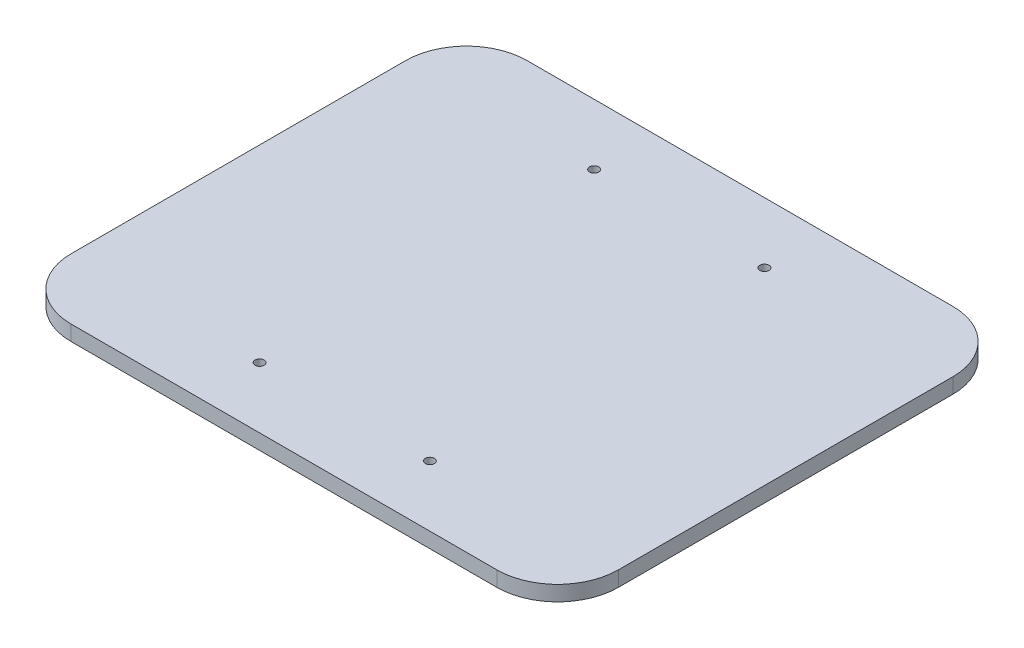
SolidWorks part; units mm, degrees
material "Acrílico (médio-alto impacto)"
ref_plane "Plano frontal" through (0, 0, 0) normal (0, 0, 1) x (1, 0, 0)
ref_plane "Plano superior" through (0, 0, 0) normal (0, 1, 0) x (1, 0, 0)
ref_plane "Plano direito" through (0, 0, 0) normal (1, 0, 0) x (0, 0, -1)
sketch "Esboço1" plane through (0, 0, 0) normal (0, 1, 0) x (1, 0, 0)
  line L1 (-40.816, 183.1145) -> (99.184, 183.1145)
  line L2 (-60.816, 163.1145) -> (-60.816, 53.1145)
  line L3 (-40.816, 33.1145) -> (99.184, 33.1145)
  line L4 (119.184, 163.1145) -> (119.184, 53.1145)
  arc A0 (99.184, 183.1145) -> (119.184, 163.1145) centre (99.184, 163.1145) cw
  arc A1 (99.184, 33.1145) -> (119.184, 53.1145) centre (99.184, 53.1145) ccw
  arc A2 (-60.816, 53.1145) -> (-40.816, 33.1145) centre (-40.816, 53.1145) ccw
  arc A3 (-40.816, 183.1145) -> (-60.816, 163.1145) centre (-40.816, 163.1145) ccw
  dimension "D1" = 20
extrude "Ressalto-extrusão1" add sketch "Esboço1" along normal blind 5
sketch "Esboço2" plane through (0, 5, 0) normal (0, 1, 0) x (1, 0, 0)
  line L0 (91.4945, 56.1145) -> (66.184, 56.1145) construction
  line L1 (-0.816, 170.1145) -> (79.184, 170.1145) construction
  line L2 (86.9299, 160.1145) -> (66.184, 160.1145) construction
  line L3 (3.7486, 46.1145) -> (83.7486, 46.1145) construction
  line L4 (64.184, 158.1145) -> (64.184, 58.1145) construction
  line L5 (-8.562, 160.1145) -> (-7.816, 160.1145) construction
  line L6 (-3.9974, 56.1145) -> (-7.816, 56.1145) construction
  line L7 (-5.816, 158.1145) -> (-5.816, 58.1145) construction
  line L10 (-60.816, 163.1145) -> (-60.816, 53.1145) construction
  line L11 (119.184, 53.1145) -> (119.184, 163.1145) construction
  line L12 (99.184, 183.1145) -> (-40.816, 183.1145) construction
  line L14 (-40.816, 33.1145) -> (99.184, 33.1145) construction
  arc A0 (88.8664, 162.6145) -> (79.184, 170.1145) centre (79.184, 160.1145) ccw construction
  arc A1 (83.7486, 46.1145) -> (93.431, 53.6145) centre (83.7486, 56.1145) ccw construction
  arc A2 (-10.4985, 162.6145) -> (-0.816, 170.1145) centre (-0.816, 160.1145) cw construction
  arc A3 (-5.9339, 53.6145) -> (3.7486, 46.1145) centre (3.7486, 56.1145) ccw construction
  arc A4 (91.4945, 56.1145) -> (93.431, 53.6145) centre (91.4945, 54.1145) cw construction
  arc A5 (64.184, 58.1145) -> (66.184, 56.1145) centre (66.184, 58.1145) ccw construction
  arc A6 (86.9299, 160.1145) -> (88.8664, 162.6145) centre (86.9299, 162.1145) ccw construction
  arc A7 (64.184, 158.1145) -> (66.184, 160.1145) centre (66.184, 158.1145) cw construction
  arc A8 (-7.816, 160.1145) -> (-5.816, 158.1145) centre (-7.816, 158.1145) cw construction
  arc A9 (-8.562, 160.1145) -> (-10.4985, 162.6145) centre (-8.562, 162.1145) cw construction
  arc A10 (-7.816, 56.1145) -> (-5.816, 58.1145) centre (-7.816, 58.1145) ccw construction
  arc A11 (-3.9974, 56.1145) -> (-5.9339, 53.6145) centre (-3.9974, 54.1145) ccw construction
  circle A12 centre (1.184, 163.1145) radius 1.5
  circle A13 centre (57.184, 163.1145) radius 1.5
  circle A14 centre (57.184, 53.1145) radius 1.5
  circle A15 centre (1.184, 53.1145) radius 1.5
  dimension "D1" = 10
  dimension "D2" = 2
  dimension "D9" = 7
  dimension "D10" = 7
  dimension "D11" = 3
  dimension "D12" = 7
  dimension "D13" = 7
  dimension "D14" = 3
  dimension "D15" = 7
  dimension "D16" = 7
  dimension "D17" = 3
  dimension "D3" = 100
  dimension "D4" = 55
  dimension "D5" = 100
  dimension "D6" = 55
  dimension "D7" = 13
  dimension "D8" = 13
extrude "Corte-extrusão1" cut sketch "Esboço2" against normal blind 10
